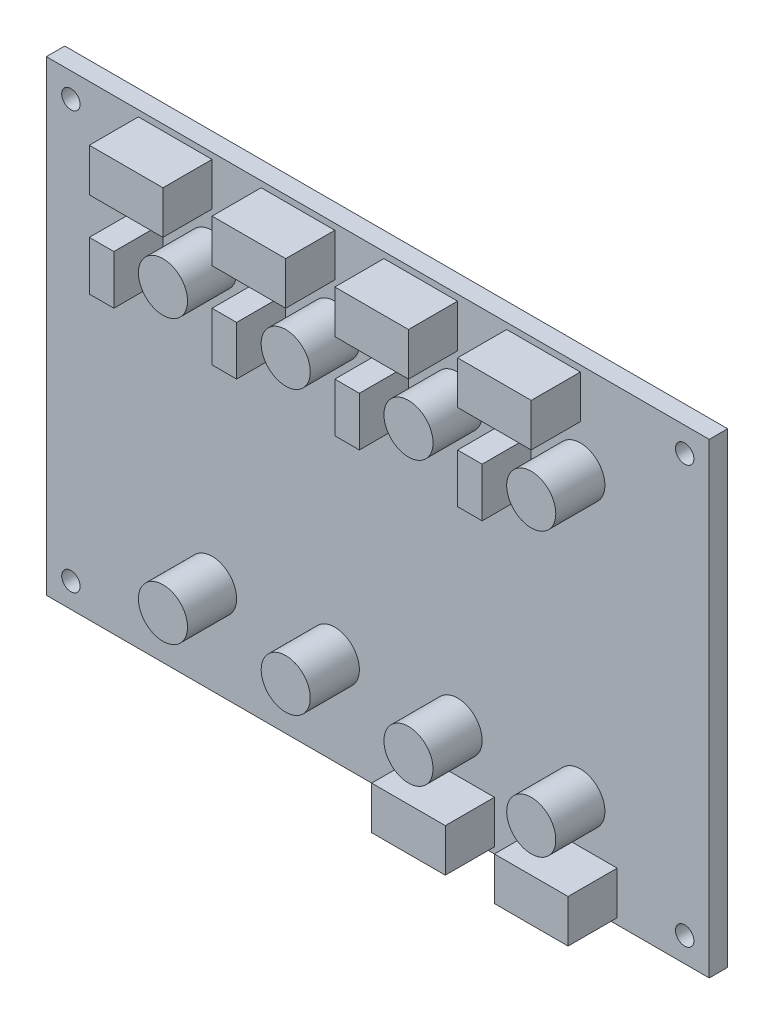
SolidWorks part; units mm, degrees
ref_plane "前视基准面" through (0, 0, 0) normal (0, 0, 1) x (1, 0, 0)
ref_plane "上视基准面" through (0, 0, 0) normal (0, 1, 0) x (1, 0, 0)
ref_plane "右视基准面" through (0, 0, 0) normal (1, 0, 0) x (0, 0, -1)
sketch "草图1" plane through (0, 0, 0) normal (0, 0, 1) x (1, 0, 0)
  line L1 (-54, 38) -> (54, 38)
  line L2 (-54, 38) -> (-54, -38)
  line L3 (-54, -38) -> (54, -38)
  line L4 (54, 38) -> (54, -38)
  line L5 (0, -38) -> (0, 38) construction
  line L6 (-54, 0) -> (54, 0) construction
  line L7 (-50, 34) -> (50, 34) construction
  line L8 (-50, 34) -> (-50, -34) construction
  line L9 (-50, -34) -> (50, -34) construction
  line L10 (50, 34) -> (50, -34) construction
  line L11 (0, -34) -> (0, 34) construction
  line L12 (-50, 0) -> (50, 0) construction
  circle A0 centre (-50, 34) radius 1.5
  circle A1 centre (50, 34) radius 1.5
  circle A2 centre (50, -34) radius 1.5
  circle A3 centre (-50, -34) radius 1.5
  point P0 (0, 0)
  point P4 (0, 0)
  dimension "D5" = 3
  dimension "D6" = 3
  dimension "D7" = 3
  dimension "D8" = 3
  dimension "D1" = 108
  dimension "D2" = 76
  dimension "D3" = 4
  dimension "D4" = 4
extrude "凸台-拉伸1" add sketch "草图1" along normal blind 3
sketch "草图2" plane through (0, 0, 3) normal (0, 0, 1) x (1, 0, 0)
  line L0 (54, 38) -> (-54, 38) construction
  line L1 (-39, 37) -> (-27, 37)
  line L2 (-39, 37) -> (-39, 30)
  line L3 (-39, 30) -> (-27, 30)
  line L4 (-27, 37) -> (-27, 30)
  line L5 (-19, 37) -> (-7, 37)
  line L6 (-19, 37) -> (-19, 30)
  line L7 (-19, 30) -> (-7, 30)
  line L8 (-7, 37) -> (-7, 30)
  line L9 (1, 37) -> (13, 37)
  line L10 (1, 37) -> (1, 30)
  line L11 (1, 30) -> (13, 30)
  line L12 (13, 37) -> (13, 30)
  line L13 (21, 37) -> (33, 37)
  line L14 (21, 37) -> (21, 30)
  line L15 (21, 30) -> (33, 30)
  line L16 (33, 37) -> (33, 30)
  line L17 (-54, 38) -> (-54, -38) construction
  line L18 (0, 0) -> (44.6693, 0) construction
  line L19 (-39, 24) -> (-35, 24)
  line L20 (-39, 24) -> (-39, 16)
  line L21 (-39, 16) -> (-35, 16)
  line L22 (-35, 24) -> (-35, 16)
  line L23 (-19, 24) -> (-15, 24)
  line L24 (-19, 24) -> (-19, 16)
  line L25 (-19, 16) -> (-15, 16)
  line L26 (-15, 24) -> (-15, 16)
  line L27 (1, 24) -> (5, 24)
  line L28 (1, 24) -> (1, 16)
  line L29 (1, 16) -> (5, 16)
  line L30 (5, 24) -> (5, 16)
  line L31 (21, 24) -> (25, 24)
  line L32 (21, 24) -> (21, 16)
  line L33 (21, 16) -> (25, 16)
  line L34 (25, 24) -> (25, 16)
  line L35 (-54, -38) -> (54, -38) construction
  line L36 (27, -30) -> (39, -30)
  line L37 (27, -30) -> (27, -37)
  line L38 (27, -37) -> (39, -37)
  line L39 (39, -30) -> (39, -37)
  line L40 (7, -30) -> (19, -30)
  line L41 (7, -30) -> (7, -37)
  line L42 (7, -37) -> (19, -37)
  line L43 (19, -30) -> (19, -37)
  line L44 (54, -38) -> (54, 38) construction
  circle A0 centre (-27, 23) radius 4
  circle A1 centre (-7, 23) radius 4
  circle A2 centre (13, 23) radius 4
  circle A3 centre (33, 23) radius 4
  circle A4 centre (33, -23) radius 4
  circle A5 centre (13, -23) radius 4
  circle A6 centre (-7, -23) radius 4
  circle A7 centre (-27, -23) radius 4
  dimension "D13" = 8
  dimension "D14" = 8
  dimension "D15" = 8
  dimension "D16" = 8
  dimension "D1" = 1
  dimension "D2" = 1
  dimension "D3" = 1
  dimension "D4" = 1
  dimension "D5" = 15
  dimension "D6" = 8
  dimension "D7" = 8
  dimension "D8" = 8
  dimension "D9" = 7
  dimension "D10" = 7
  dimension "D11" = 7
  dimension "D12" = 7
  dimension "D17" = 15
  dimension "D18" = 6
  dimension "D19" = 4
  dimension "D20" = 8
  dimension "D21" = 15
  dimension "D22" = 15
  dimension "D23" = 15
  dimension "D24" = 15
  dimension "D25" = 12
  dimension "D26" = 12
  dimension "D27" = 12
  dimension "D28" = 12
  dimension "D29" = 4
  dimension "D30" = 8
  dimension "D31" = 4
  dimension "D32" = 8
  dimension "D33" = 4
  dimension "D34" = 8
  dimension "D35" = 7
  dimension "D36" = 12
  dimension "D37" = 7
  dimension "D38" = 12
  dimension "D39" = 1
  dimension "D40" = 1
  dimension "D41" = 15
  dimension "D42" = 8
extrude "凸台-拉伸2" add sketch "草图2" along normal blind 8
